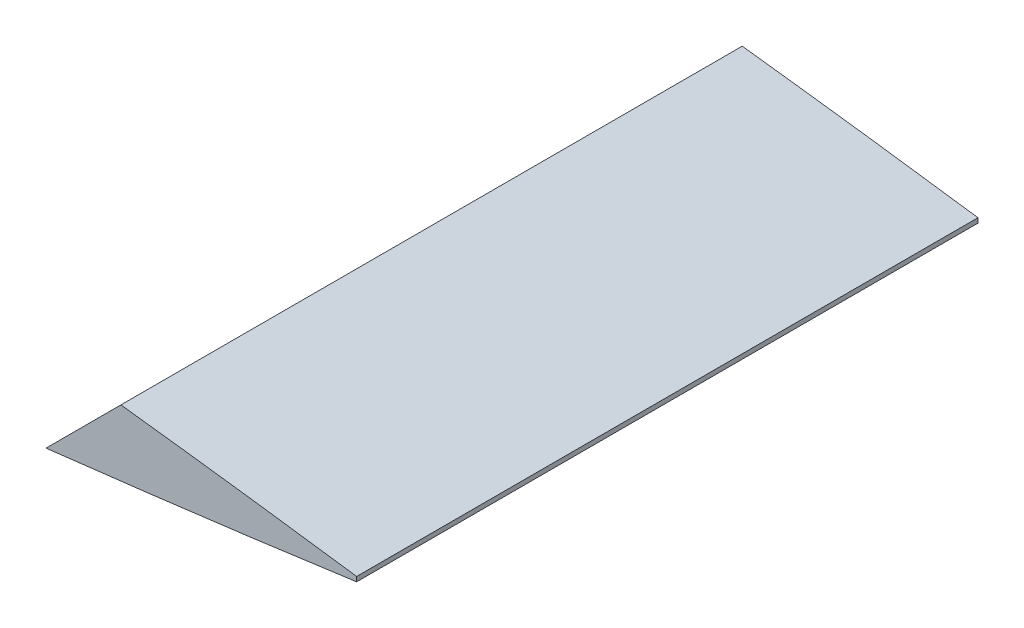
SolidWorks part; units mm, degrees
material "Balsa"
ref_plane "Front Plane" through (0, 0, 0) normal (0, 0, 1) x (1, 0, 0)
ref_plane "Top Plane" through (0, 0, 0) normal (0, 1, 0) x (1, 0, 0)
ref_plane "Right Plane" through (0, 0, 0) normal (1, 0, 0) x (0, 0, -1)
sketch "Sketch5" plane through (0, 0, 0) normal (0, 0, 1) x (1, 0, 0)
  line L1 (300, 0.378) -> (300, -0.378)
  spline S1 degree 3 poles (300, 0.378) (299.2704, 0.4794) (297.2347, 0.7625) (293.6597, 1.2577) (289.1124, 1.8742) (284.0808, 2.5445) (278.752, 3.2381) (273.2659, 3.9349) (267.706, 4.629) (262.1146, 5.3131) (256.5083, 5.9822) (250.8917, 6.638) (245.2696, 7.2818) (239.6473, 7.9122) (234.0251, 8.527) (228.3991, 9.1262) (222.7683, 9.7131) (217.1359, 10.2875) (211.5054, 10.8469) (205.8776, 11.3916) (200.2515, 11.9209) (194.6264, 12.4346) (189.0028, 12.9319) (183.3815, 13.4131) (177.7632, 13.8764) (172.1483, 14.3212) (166.5375, 14.7478) (160.9317, 15.1542) (155.3317, 15.5391) (149.7375, 15.9026) (144.1487, 16.2418) (138.5657, 16.5574) (132.9909, 16.8474) (127.4274, 17.1102) (121.8776, 17.3439) (116.3408, 17.5453) (110.8155, 17.7127) (105.3013, 17.8445) (99.8006, 17.9401) (94.3174, 17.9966) (88.8558, 18.0101) (83.4186, 17.9792) (78.0085, 17.8992) (72.6285, 17.767) (67.2827, 17.5794) (61.9774, 17.3315) (56.7207, 17.021) (51.5252, 16.641) (46.4082, 16.1902) (41.3942, 15.6617) (36.5157, 15.054) (31.819, 14.3656) (27.3662, 13.6035) (23.2352, 12.7826) (19.5026, 11.9203) (16.2183, 11.0446) (13.3892, 10.1751) (10.9849, 9.3335) (8.9616, 8.5221) (7.2673, 7.747) (5.8461, 7.0106) (4.6477, 6.3006) (3.6282, 5.6065) (2.7519, 4.9266) (2.0063, 4.2499) (1.3906, 3.5703) (0.901, 2.8909) (0.5293, 2.2202) (0.2605, 1.5665) (0.0857, 0.931) (-0.0035, 0.309) (-0.0035, -0.309) (0.0857, -0.931) (0.2605, -1.5665) (0.5293, -2.2202) (0.901, -2.8909) (1.3906, -3.5703) (2.0063, -4.2499) (2.7519, -4.9266) (3.6282, -5.6065) (4.6477, -6.3006) (5.8461, -7.0106) (7.2673, -7.747) (8.9616, -8.5221) (10.9849, -9.3335) (13.3892, -10.1751) (16.2183, -11.0446) (19.5026, -11.9203) (23.2352, -12.7826) (27.3661, -13.6036) (31.8191, -14.3651) (36.5156, -15.0541) (41.3942, -15.6616) (46.4082, -16.1902) (51.5252, -16.641) (56.7207, -17.021) (61.9774, -17.3315) (67.2827, -17.5794) (72.6285, -17.767) (78.0085, -17.8992) (83.4186, -17.9792) (88.8558, -18.0101) (94.3174, -17.9966) (99.8006, -17.9401) (105.3013, -17.8445) (110.8155, -17.7127) (116.3408, -17.5453) (121.8776, -17.3439) (127.4274, -17.1102) (132.9909, -16.8474) (138.5657, -16.5574) (144.1487, -16.2418) (149.7375, -15.9026) (155.3317, -15.5391) (160.9317, -15.1542) (166.5375, -14.7478) (172.1483, -14.3212) (177.7632, -13.8764) (183.3815, -13.4131) (189.0028, -12.9319) (194.6264, -12.4346) (200.2515, -11.9209) (205.8776, -11.3916) (211.5054, -10.8469) (217.1359, -10.2875) (222.7683, -9.7131) (228.3991, -9.1262) (234.0251, -8.527) (239.6473, -7.9122) (245.2696, -7.2818) (250.8917, -6.638) (256.5083, -5.9822) (262.1146, -5.3131) (267.706, -4.629) (273.2659, -3.9349) (278.752, -3.2381) (284.0808, -2.5445) (289.1124, -1.8742) (293.6597, -1.2577) (297.2347, -0.7625) (299.2704, -0.4794) (300, -0.378) knots 0 0 0 0 0.003612 0.010079 0.017699 0.026115 0.034971 0.04405 0.053234 0.062448 0.071674 0.080921 0.090178 0.099424 0.108664 0.117912 0.12717 0.136427 0.145675 0.154916 0.164153 0.173387 0.182616 0.191838 0.201053 0.21026 0.219459 0.228647 0.237822 0.246985 0.256137 0.265279 0.274407 0.283512 0.292592 0.301646 0.310682 0.319699 0.328695 0.33766 0.346589 0.355477 0.364323 0.373122 0.381868 0.390553 0.399166 0.40769 0.416098 0.424355 0.432412 0.440205 0.447631 0.454564 0.460855 0.466413 0.471229 0.475366 0.478901 0.481915 0.484499 0.486747 0.488741 0.490543 0.492182 0.493673 0.495032 0.496279 0.497425 0.49849 0.499503 0.500497 0.50151 0.502575 0.503721 0.504968 0.506327 0.507818 0.509457 0.511259 0.513253 0.515501 0.518085 0.521099 0.524634 0.528771 0.533587 0.539145 0.545436 0.55237 0.559795 0.567588 0.575645 0.583902 0.59231 0.600834 0.609447 0.618132 0.626878 0.635677 0.644523 0.653411 0.66234 0.671305 0.680301 0.689318 0.698354 0.707408 0.716488 0.725593 0.734721 0.743863 0.753015 0.762178 0.771353 0.780541 0.78974 0.798947 0.808162 0.817384 0.826613 0.835847 0.845084 0.854325 0.863573 0.87283 0.882088 0.891336 0.900576 0.909822 0.919079 0.928326 0.937552 0.946766 0.95595 0.965029 0.973885 0.982301 0.989921 0.996388 1 1 1 1
  dimension "Tail chord" = 300
extrude "Boss-Extrude1" add sketch "Sketch5" along normal blind 100
ref_plane "Plane1" through (0, 0, 110) normal (0, 0, 1) x (1, 0, 0)
curve "Curve6"
  spline degree 3 poles (298.242, -0.1932, 0) (300.4407, 0, 0) (298.242, 0.1932, 0) (296.4349, 0.5367, 0) (292.0253, 1.0976, 0) (286.5771, 1.8592, 0) (279.4156, 2.8001, 0) (270.9173, 3.8949, 0) (261.066, 5.1159, 0) (250.0071, 6.4339, 0) (237.8495, 7.8187, 0) (224.7304, 9.2395, 0) (210.7923, 10.6647, 0) (196.1883, 12.0613, 0) (181.0783, 13.3946, 0) (165.6277, 14.6278, 0) (150.0058, 15.7225, 0) (134.3834, 16.6392, 0) (118.9317, 17.3387, 0) (103.8195, 17.7845, 0) (89.2123, 17.9443, 0) (75.2698, 17.7935, 0) (62.1444, 17.3161, 0) (49.9793, 16.5075, 0) (38.907, 15.374, 0) (29.0471, 13.9333, 0) (20.5034, 12.2128, 0) (13.3641, 10.246, 0) (7.6828, 8.0707, 0) (3.4992, 5.7028, 0) (0.7348, 3.1014, 0) (-0.3264, 0, 0) (0.7348, -3.1014, 0) (3.4992, -5.7028, 0) (7.6828, -8.0707, 0) (13.3641, -10.246, 0) (20.5034, -12.2128, 0) (29.0471, -13.9333, 0) (38.907, -15.374, 0) (49.9793, -16.5075, 0) (62.1444, -17.3161, 0) (75.2698, -17.7935, 0) (89.2123, -17.9443, 0) (103.8195, -17.7845, 0) (118.9317, -17.3387, 0) (134.3834, -16.6392, 0) (150.0058, -15.7225, 0) (165.6277, -14.6278, 0) (181.0783, -13.3946, 0) (196.1883, -12.0613, 0) (210.7923, -10.6647, 0) (224.7304, -9.2395, 0) (237.8495, -7.8187, 0) (250.0071, -6.4339, 0) (261.066, -5.1159, 0) (270.9173, -3.8949, 0) (279.4156, -2.8001, 0) (286.5771, -1.8592, 0) (292.0253, -1.0976, 0) (296.4349, -0.5367, 0) (298.242, -0.1932, 0) (300.4407, 0, 0) (298.242, 0.1932, 0) knots -0.012119 -0.005412 -0.001357 0 0.001357 0.005412 0.012119 0.021403 0.033159 0.047255 0.063534 0.081814 0.101892 0.123547 0.146538 0.170613 0.195504 0.220938 0.246636 0.272314 0.297694 0.3225 0.346466 0.36934 0.390884 0.410879 0.429129 0.445462 0.459736 0.471848 0.481751 0.489494 0.495334 0.5 0.504666 0.510506 0.518249 0.528152 0.540264 0.554538 0.570871 0.589121 0.609116 0.63066 0.653534 0.6775 0.702306 0.727686 0.753364 0.779062 0.804496 0.829387 0.853462 0.876453 0.898108 0.918186 0.936466 0.952745 0.966841 0.978597 0.987881 0.994588 0.998643 1 1.001357 1.005412 1.012119 periodic
sketch "Sketch8" plane through (0, 0, 0) normal (0, 0, 1) x (1, 0, 0)
  spline S0 degree 3 poles (298.242, -0.1932) (300.4407, 0) (298.242, 0.1932) (296.4349, 0.5367) (292.0253, 1.0976) (286.5771, 1.8592) (279.4156, 2.8001) (270.9173, 3.8949) (261.066, 5.1159) (250.0071, 6.4339) (237.8495, 7.8187) (224.7304, 9.2395) (210.7923, 10.6647) (196.1883, 12.0613) (181.0783, 13.3946) (165.6277, 14.6278) (150.0058, 15.7225) (134.3834, 16.6392) (118.9317, 17.3387) (103.8195, 17.7845) (89.2123, 17.9443) (75.2698, 17.7935) (62.1444, 17.3161) (49.9793, 16.5075) (38.907, 15.374) (29.0471, 13.9333) (20.5034, 12.2128) (13.3641, 10.246) (7.6828, 8.0707) (3.4992, 5.7028) (0.7348, 3.1014) (-0.3264, 0) (0.7348, -3.1014) (3.4992, -5.7028) (7.6828, -8.0707) (13.3641, -10.246) (20.5034, -12.2128) (29.0471, -13.9333) (38.907, -15.374) (49.9793, -16.5075) (62.1444, -17.3161) (75.2698, -17.7935) (89.2123, -17.9443) (103.8195, -17.7845) (118.9317, -17.3387) (134.3834, -16.6392) (150.0058, -15.7225) (165.6277, -14.6278) (181.0783, -13.3946) (196.1883, -12.0613) (210.7923, -10.6647) (224.7304, -9.2395) (237.8495, -7.8187) (250.0071, -6.4339) (261.066, -5.1159) (270.9173, -3.8949) (279.4156, -2.8001) (286.5771, -1.8592) (292.0253, -1.0976) (296.4349, -0.5367) (298.242, -0.1932) (300.4407, 0) (298.242, 0.1932) knots -0.012119 -0.005412 -0.001357 0 0.001357 0.005412 0.012119 0.021403 0.033159 0.047255 0.063534 0.081814 0.101892 0.123547 0.146538 0.170613 0.195504 0.220938 0.246636 0.272314 0.297694 0.3225 0.346466 0.36934 0.390884 0.410879 0.429129 0.445462 0.459736 0.471848 0.481751 0.489494 0.495334 0.5 0.504666 0.510506 0.518249 0.528152 0.540264 0.554538 0.570871 0.589121 0.609116 0.63066 0.653534 0.6775 0.702306 0.727686 0.753364 0.779062 0.804496 0.829387 0.853462 0.876453 0.898108 0.918186 0.936466 0.952745 0.966841 0.978597 0.987881 0.994588 0.998643 1 1.001357 1.005412 1.012119 only from (300, 0) to (300, 0) construction
  spline S1 degree 3 poles (298.242, -0.1932) (300.4407, 0) (298.242, 0.1932) (296.4349, 0.5367) (292.0253, 1.0976) (286.5771, 1.8592) (279.4156, 2.8001) (270.9173, 3.8949) (261.066, 5.1159) (250.0071, 6.4339) (237.8495, 7.8187) (224.7304, 9.2395) (210.7923, 10.6647) (196.1883, 12.0613) (181.0783, 13.3946) (165.6277, 14.6278) (150.0058, 15.7225) (134.3834, 16.6392) (118.9317, 17.3387) (103.8195, 17.7845) (89.2123, 17.9443) (75.2698, 17.7935) (62.1444, 17.3161) (49.9793, 16.5075) (38.907, 15.374) (29.0471, 13.9333) (20.5034, 12.2128) (13.3641, 10.246) (7.6828, 8.0707) (3.4992, 5.7028) (0.7348, 3.1014) (-0.3264, 0) (0.7348, -3.1014) (3.4992, -5.7028) (7.6828, -8.0707) (13.3641, -10.246) (20.5034, -12.2128) (29.0471, -13.9333) (38.907, -15.374) (49.9793, -16.5075) (62.1444, -17.3161) (75.2698, -17.7935) (89.2123, -17.9443) (103.8195, -17.7845) (118.9317, -17.3387) (134.3834, -16.6392) (150.0058, -15.7225) (165.6277, -14.6278) (181.0783, -13.3946) (196.1883, -12.0613) (210.7923, -10.6647) (224.7304, -9.2395) (237.8495, -7.8187) (250.0071, -6.4339) (261.066, -5.1159) (270.9173, -3.8949) (279.4156, -2.8001) (286.5771, -1.8592) (292.0253, -1.0976) (296.4349, -0.5367) (298.242, -0.1932) (300.4407, 0) (298.242, 0.1932) knots -0.012119 -0.005412 -0.001357 0 0.001357 0.005412 0.012119 0.021403 0.033159 0.047255 0.063534 0.081814 0.101892 0.123547 0.146538 0.170613 0.195504 0.220938 0.246636 0.272314 0.297694 0.3225 0.346466 0.36934 0.390884 0.410879 0.429129 0.445462 0.459736 0.471848 0.481751 0.489494 0.495334 0.5 0.504666 0.510506 0.518249 0.528152 0.540264 0.554538 0.570871 0.589121 0.609116 0.63066 0.653534 0.6775 0.702306 0.727686 0.753364 0.779062 0.804496 0.829387 0.853462 0.876453 0.898108 0.918186 0.936466 0.952745 0.966841 0.978597 0.987881 0.994588 0.998643 1 1.001357 1.005412 1.012119 only from (300, 0) to (300, 0)
sketch "Sketch9" plane through (0, 0, 0) normal (0, 1, 0) x (1, 0, 0)
  line L0 (0.0001, -100) -> (300, -100) construction
  line L1 (300, 0) -> (250, 0)
  line L2 (300, 0) -> (300, -100)
  line L3 (300, -100) -> (250, -100)
  line L4 (250, 0) -> (250, -100)
  dimension "D1" = 50
extrude "Cut-Extrude8" cut sketch "Sketch9" against normal through all and the other way through all flip side to cut
sketch "Sketch10" plane through (0, 0, 0) normal (0, 0, 1) x (1, 0, 0)
  line L0 (250, -6.7388) -> (280, 23.2612)
  line L1 (280, 23.2612) -> (250, 23.2612)
  line L2 (250, 23.2612) -> (250, -6.7388)
  dimension "D1" = 45
  dimension "D2" = 30
extrude "Cut-Extrude9" cut sketch "Sketch10" along normal through all
equation "\"Chord\"= 300mm'Tail chord"
equation "\"Tail chord@Sketch5\"=\"Chord\""
